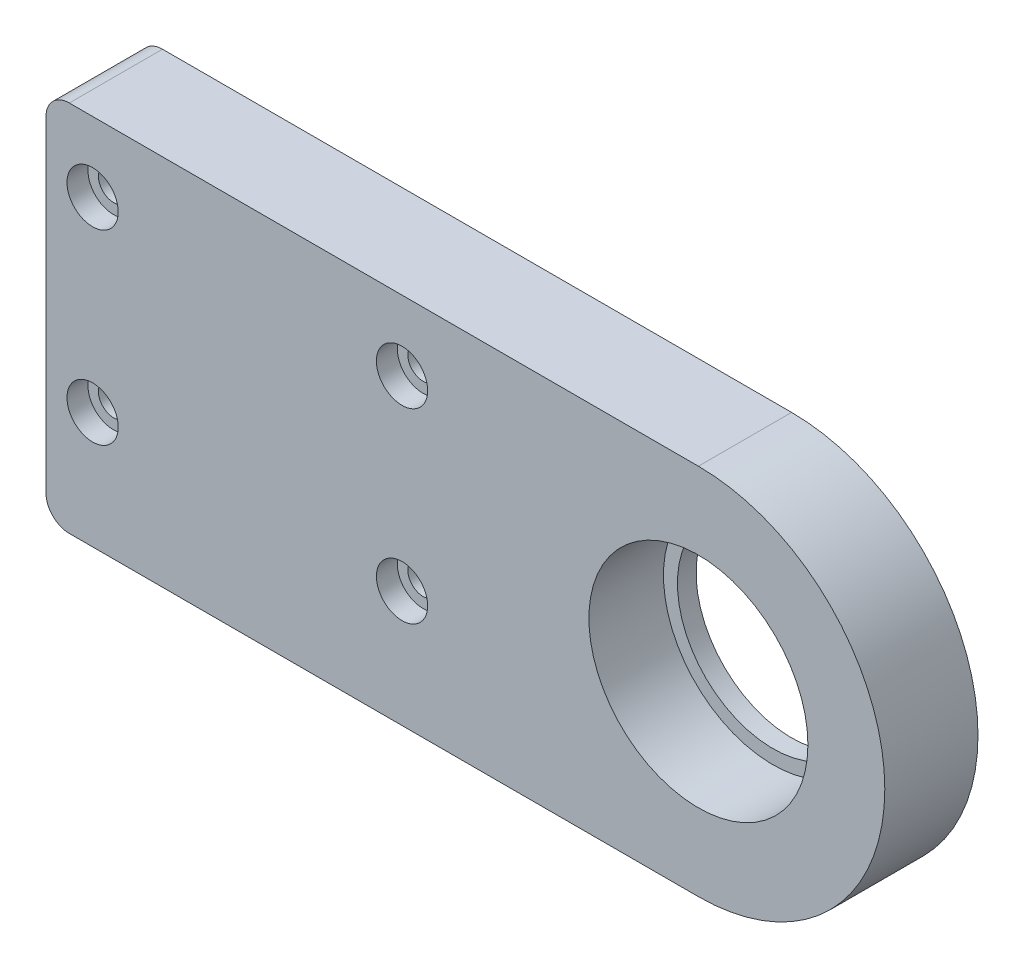
SolidWorks part; units mm, degrees
material "5052-H32"
ref_plane "Front Plane" through (0, 0, 0) normal (0, 0, 1) x (1, 0, 0)
ref_plane "Top Plane" through (0, 0, 0) normal (0, 1, 0) x (1, 0, 0)
ref_plane "Right Plane" through (0, 0, 0) normal (1, 0, 0) x (0, 0, -1)
sketch "Sketch1" plane through (0, 0, 0) normal (0, 0, 1) x (1, 0, 0)
  line L0 (0, 40) -> (-140, 40)
  line L1 (-140, 40) -> (-140, -40)
  line L2 (-140, -40) -> (0, -40)
  arc A1 (0, -40) -> (0, 40) centre (0, 0) ccw
  circle A2 centre (0, 0) radius 20.5
  dimension "D2" = 41
  dimension "D1" = 80
  dimension "D3" = 140
  dimension "D4" = 0
extrude "Boss-Extrude1" add sketch "Sketch1" along normal blind 20
sketch "Sketch2" plane through (0, 0, 20) normal (0, 0, 1) x (1, 0, 0)
  circle A0 centre (0, 0) radius 23.5
  dimension "D1" = 47
extrude "Cut-Extrude1" cut sketch "Sketch2" against normal blind 16
sketch "Sketch4" plane through (0, 0, 0) normal (0, 0, -1) x (-1, 0, 0)
  line L0 (140, 40) -> (140, -40) construction
  line L1 (140, -19) -> (55, -19)
  line L2 (140, -19) -> (140, -11)
  line L3 (140, -11) -> (55, -11)
  line L4 (55, -19) -> (55, -11)
  line L6 (140, 21) -> (55, 21)
  line L7 (140, 21) -> (140, 29)
  line L8 (140, 29) -> (55, 29)
  line L9 (55, 21) -> (55, 29)
  point P10 (140, 25)
  point P11 (140, -15)
  point P12 (55, 25)
  dimension "D1" = 8
  dimension "D2" = 8
  dimension "D3" = 40
  dimension "D4" = 25
  dimension "D5" = 85
extrude "Boss-Extrude2" add sketch "Sketch4" along normal blind 3
sketch "Sketch3" plane through (0, 0, 20) normal (0, 0, 1) x (1, 0, 0)
  line L0 (-140, 40) -> (-140, -40) construction
  circle A0 centre (-63.6, 25) radius 3.25
  circle A1 centre (-130, 25) radius 3.25
  circle A2 centre (-130, -15) radius 3.25
  circle A3 centre (-63.6, -15) radius 3.25
  dimension "D5" = 6.5
  dimension "D1" = 40
  dimension "D2" = 25
  dimension "D3" = 10
  dimension "D4" = 66.4
extrude "Cut-Extrude2" cut sketch "Sketch3" against normal through all
sketch "Sketch5" plane through (0, 0, 20) normal (0, 0, 1) x (1, 0, 0)
  circle A0 centre (-130, 25) radius 5.5
  circle A1 centre (-63.6, 25) radius 5.5
  circle A2 centre (-63.6, -15) radius 5.5
  circle A3 centre (-130, -15) radius 5.5
  dimension "D1" = 11
extrude "Cut-Extrude3" cut sketch "Sketch5" against normal blind 4.5
fillet "Fillet1" radius 5 2 edges at (-140, 40, 10) (-140, -40, 10)
